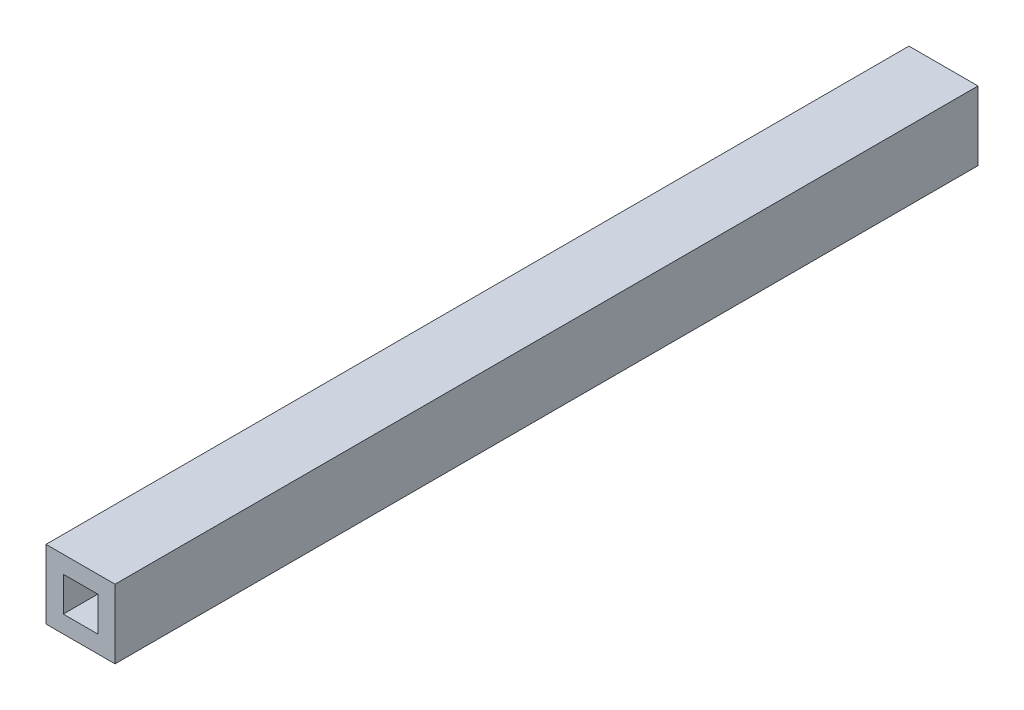
SolidWorks part; units mm, degrees
material "6063-O"
ref_plane "Front Plane" through (0, 0, 0) normal (0, 0, 1) x (1, 0, 0)
ref_plane "Top Plane" through (0, 0, 0) normal (0, 1, 0) x (1, 0, 0)
ref_plane "Right Plane" through (0, 0, 0) normal (1, 0, 0) x (0, 0, -1)
sketch "Sketch1" plane through (0, 0, 0) normal (0, 0, 1) x (1, 0, 0)
  line L1 (-10, -10) -> (10, -10)
  line L2 (-10, -10) -> (-10, 10)
  line L3 (-10, 10) -> (10, 10)
  line L4 (10, -10) -> (10, 10)
  line L5 (-10, -10) -> (10, 10) construction
  line L6 (-10, 10) -> (10, -10) construction
  point P0 (0, 0)
  dimension "D1" = 20
extrude "Extrude-Thin1" add sketch "Sketch1" along normal blind 250 thin thin type one direction reverse wall 5
